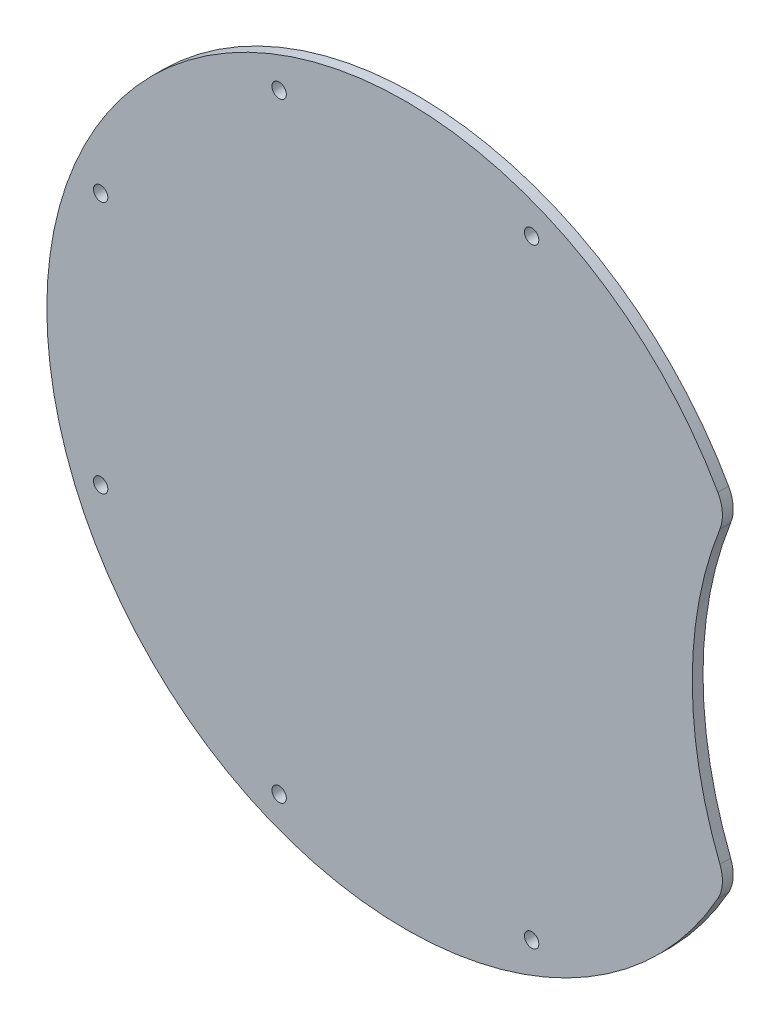
SolidWorks part; units mm, degrees
ref_plane "Alzado" through (0, 0, 0) normal (0, 0, 1) x (1, 0, 0)
ref_plane "Planta" through (0, 0, 0) normal (0, 1, 0) x (1, 0, 0)
ref_plane "Vista lateral" through (0, 0, 0) normal (1, 0, 0) x (0, 0, -1)
sketch "Croquis1" plane through (0, 0, 0) normal (0, 0, 1) x (1, 0, 0)
  circle A0 centre (0, 0) radius 100
  dimension "D1" = 200
extrude "Saliente-Extruir1" add sketch "Croquis1" along normal blind 3
sketch "Croquis3" plane through (0, 0, 3) normal (0, 0, 1) x (1, 0, 0)
  line L0 (0, 0) -> (190, 0) construction
  circle A0 centre (190, 0) radius 110
  dimension "D1" = 220
  dimension "D2" = 190
extrude "Cortar-Extruir1" cut sketch "Croquis3" against normal blind 3
fillet "Redondeo1" radius 10 2 edges at (89.4737, -44.6594, 1.5) (89.4737, 44.6594, 1.5)
sketch "Croquis4" plane through (0, 0, 0) normal (0, 0, -1) x (-1, 0, 0)
  line L2 (-38.2683, 92.388) -> (-35.2069, 84.9969) construction
  arc A0 (-87.1345, -49.0671) -> (-87.1345, 49.0671) centre (0, 0) ccw construction
  circle A1 centre (-35.2069, 84.9969) radius 2
  circle A2 centre (35.2069, 84.9969) radius 2
  circle A3 centre (84.9969, 35.2069) radius 2
  circle A4 centre (84.9969, -35.2069) radius 2
  circle A5 centre (35.2069, -84.9969) radius 2
  circle A6 centre (-35.2069, -84.9969) radius 2
  circle A9 centre (-84.9969, -35.2069) radius 2 [skipped]
  circle A10 centre (-84.9969, 35.2069) radius 2 [skipped]
  point P25 (0, 0)
  dimension "D2" = 4
  dimension "D3" = 35.2069
  dimension "D4" = 8
  dimension "D1" = 8
extrude "Cortar-Extruir2" cut sketch "Croquis4" against normal through all
